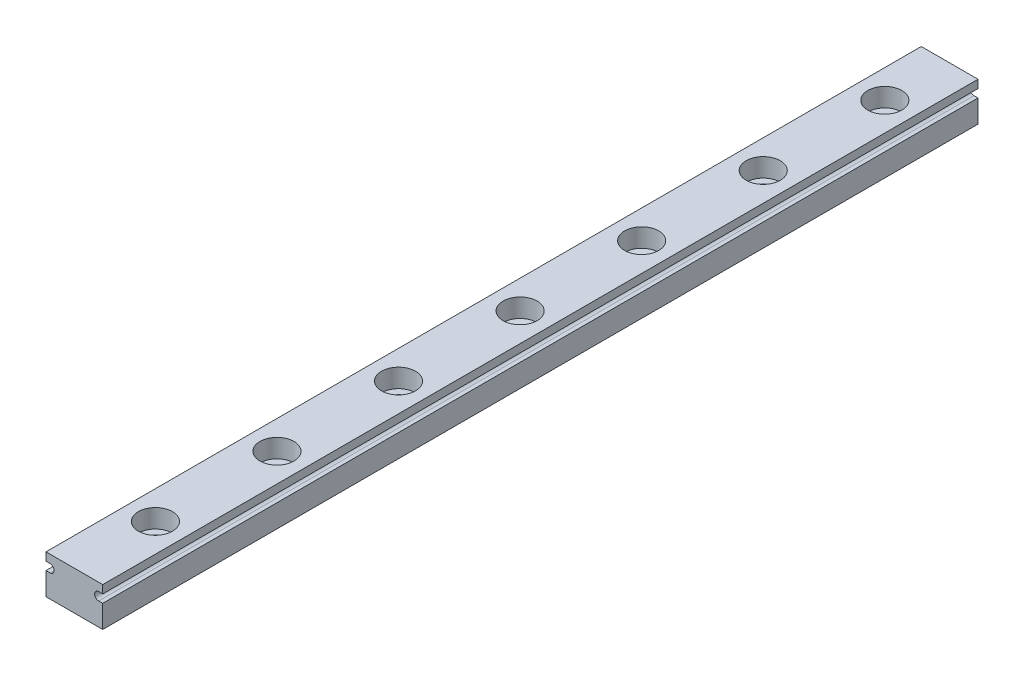
SolidWorks part; units mm, degrees
ref_plane "Front Plane" through (0, 0, 0) normal (0, 0, 1) x (1, 0, 0)
ref_plane "Top Plane" through (0, 0, 0) normal (0, 1, 0) x (1, 0, 0)
ref_plane "Right Plane" through (0, 0, 0) normal (1, 0, 0) x (0, 0, -1)
sketch "Sketch1" plane through (0, 0, 0) normal (0, 0, 1) x (1, 0, 0)
  line L0 (-3.5, 0) -> (3.5, 0)
  line L1 (0, 0) -> (0, 4.8) construction
  line L2 (-3.5, 4.8) -> (3.5, 4.8)
  line L3 (3.5, 4.8) -> (3.5, 3.8)
  line L4 (-3.5, 4.8) -> (-3.5, 3.8)
  line L5 (3, 3.3) -> (3.5, 3.3) construction
  line L6 (3, 3.8) -> (3.5, 3.8)
  line L7 (3, 2.8) -> (3.5, 2.8)
  line L8 (3.5, 2.8) -> (3.5, 0)
  line L9 (-3, 2.8) -> (-3.5, 2.8)
  line L10 (-3, 3.8) -> (-3.5, 3.8)
  line L11 (-3.5, 2.8) -> (-3.5, 0)
  arc A0 (3, 3.8) -> (3, 2.8) centre (3, 3.3) ccw
  arc A2 (-3, 3.8) -> (-3, 2.8) centre (-3, 3.3) cw
  point P8 (3.6788, 1.8902)
  dimension "D4" = 0.5
  dimension "D1" = 7
  dimension "D2" = 4.8
  dimension "D3" = 0.5
  dimension "D5" = 1.5
extrude "Boss-Extrude1" add sketch "Sketch1" against normal blind 108
sketch "Sketch2" plane through (0, 0, 0) normal (1, 0, 0) x (0, 0, -1)
  line L0 (10, 4.8) -> (10, 0) construction
  line L1 (108, 4.8) -> (0, 4.8) construction
  line L2 (108, 0) -> (0, 0) construction
  line L3 (7.9, 4.8) -> (7.9, 2.5)
  line L4 (7.9, 2.5) -> (8.8, 2.5)
  line L5 (8.8, 2.5) -> (8.8, 0)
  line L6 (8.8, 0) -> (10, 0)
  line L7 (7.9, 4.8) -> (10, 4.8)
  line L8 (0, 0) -> (0, 2.8) construction
  line L9 (10, 4.8) -> (10, 0)
  dimension "D1" = 2.1
  dimension "D2" = 1.2
  dimension "D3" = 2.3
  dimension "D4" = 10
revolve "Cut-Revolve1" cut sketch "Sketch2" angle 360 about L0
pattern_linear "LPattern1" count 7 spacing 15 along (0, 0, -1) of "Cut-Revolve1"
